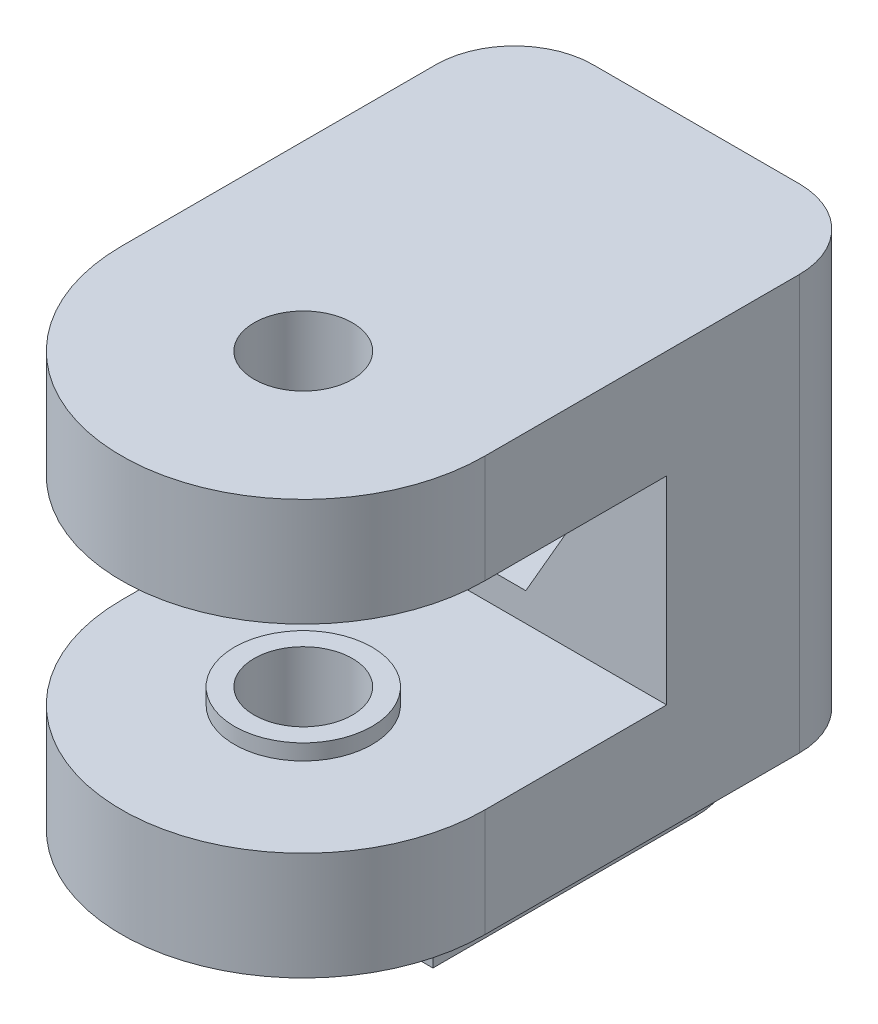
SolidWorks part; units mm, degrees
ref_plane "Front Plane" through (0, 0, 0) normal (0, 0, 1) x (1, 0, 0)
ref_plane "Top Plane" through (0, 0, 0) normal (0, 1, 0) x (1, 0, 0)
ref_plane "Right Plane" through (0, 0, 0) normal (1, 0, 0) x (0, 0, -1)
sketch "Sketch1" plane through (0, 0, 0) normal (0, 1, 0) x (1, 0, 0)
  line L0 (-9.25, 0) -> (-9.25, 20)
  line L1 (-9.25, 20) -> (9.25, 20)
  line L2 (9.25, 20) -> (9.25, 0)
  line L3 (0, 0) -> (9.25, 0) construction
  line L4 (0, 0) -> (0, 20) construction
  arc A0 (-9.25, 0) -> (9.25, 0) centre (0, 0) ccw
  arc A1 (0, 9.25) -> (-9.25, 0) centre (0, 0) ccw construction
  arc A2 (9.25, 0) -> (0, 9.25) centre (0, 0) ccw construction
  circle A3 centre (0, 0) radius 2.5
  dimension "D1" = 18.5
  dimension "D3" = 5
  dimension "D2" = 20
extrude "Boss-Extrude1" add sketch "Sketch1" along normal blind 21.1
sketch "Sketch2" plane through (9.25, 0, 0) normal (1, 0, 0) x (0, 0, -1)
  line L0 (-9.25, 10.55) -> (20, 10.55) construction
  line L1 (-9.25, 21.1) -> (-9.25, 0) construction
  line L2 (20, 21.1) -> (20, 0) construction
  line L3 (9.25, 15.6) -> (9.25, 5.5)
  line L4 (-9.25, 15.6) -> (9.25, 15.6)
  line L5 (-9.25, 15.6) -> (-9.25, 5.5)
  line L6 (-9.25, 5.5) -> (9.25, 5.5)
  point P7 (9.25, 10.55)
  dimension "D1" = 5.05
  dimension "D2" = 18.5
extrude "Cut-Extrude1" cut sketch "Sketch2" against normal through all
sketch "Sketch3" plane through (0, 0, 0) normal (0, -1, 0) x (1, 0, 0)
  line L0 (4.1, -2.5) -> (4.1, -15.9)
  line L7 (-4.1, -15.9) -> (-4.1, -2.5)
  line L8 (3.2496, -2.5) -> (4.1, -2.5)
  line L9 (0, -20) -> (0, -3.5) construction
  line L10 (-3.2496, -2.5) -> (-4.1, -2.5)
  line L11 (-4.1, -2.5) -> (-4.1, 0) construction
  line L12 (4.1, 0) -> (4.1, -2.5) construction
  line L13 (4.1, 0) -> (-4.1, 0) construction
  line L14 (9.25, -20) -> (-9.25, -20) construction
  arc A5 (-3.2496, -2.5) -> (3.2496, -2.5) centre (0, 0) ccw
  arc A6 (4.1, 0) -> (-4.1, 0) centre (0, 0) ccw construction
  arc A8 (-4.1, 0) -> (-3.2496, -2.5) centre (0, 0) ccw construction
  arc A9 (3.2496, -2.5) -> (4.1, 0) centre (0, 0) ccw construction
  arc A10 (-4.1, -15.9) -> (4.1, -15.9) centre (0, -15.9) ccw
  dimension "D1" = 8.2
  dimension "D3" = 2.5
  dimension "D2" = 1
extrude "Boss-Extrude3" add sketch "Sketch3" along normal blind 5.3
sketch "Sketch4" plane through (0, 5.5, 0) normal (0, 1, 0) x (1, 0, 0)
  circle A0 centre (0, 0) radius 3.5
  circle A1 centre (0, 0) radius 2.5 construction
  circle A2 centre (0, 0) radius 2.5
  dimension "D1" = 7
extrude "Boss-Extrude4" add sketch "Sketch4" along normal blind 0.8
ref_plane "Plane1" through (0, 10.55, 0) normal (0, 1, 0) x (1, 0, 0)
mirror "Mirror1" about plane through (0, 10.55, 0) normal (0, 1, 0) of "Boss-Extrude4"
fillet "Fillet1" radius 4 2 edges at (9.25, 10.55, -20) (-9.25, 10.55, -20)
sketch "Sketch5" plane through (0, 0, -9.25) normal (0, 0, 1) x (1, 0, 0)
  line L0 (0, 5.5) -> (0, 15.6) construction
  line L1 (9.25, 5.5) -> (-9.25, 5.5) construction
  line L2 (-9.25, 15.6) -> (9.25, 15.6) construction
  line L4 (2.0785, 6.95) -> (4.1569, 10.55)
  line L5 (4.1569, 10.55) -> (2.0785, 14.15)
  line L6 (2.0785, 14.15) -> (-2.0785, 14.15)
  line L7 (-2.0785, 14.15) -> (-4.1569, 10.55)
  line L8 (-4.1569, 10.55) -> (-2.0785, 6.95)
  line L9 (-2.0785, 6.95) -> (2.0785, 6.95)
  circle A0 centre (0, 10.55) radius 3.6 construction
  dimension "D1" = 7.2
extrude "Cut-Extrude2" cut sketch "Sketch5" against normal blind 7
sketch "Sketch6" plane through (0, 0, -16.25) normal (0, 0, 1) x (1, 0, 0)
  line L0 (0, 14.15) -> (0, 6.95) construction
  line L1 (2.0785, 14.15) -> (-2.0785, 14.15) construction
  line L2 (-2.0785, 6.95) -> (2.0785, 6.95) construction
  circle A0 centre (0, 10.55) radius 2.2
  dimension "D1" = 4.4
extrude "Cut-Extrude3" cut sketch "Sketch6" against normal blind 7
